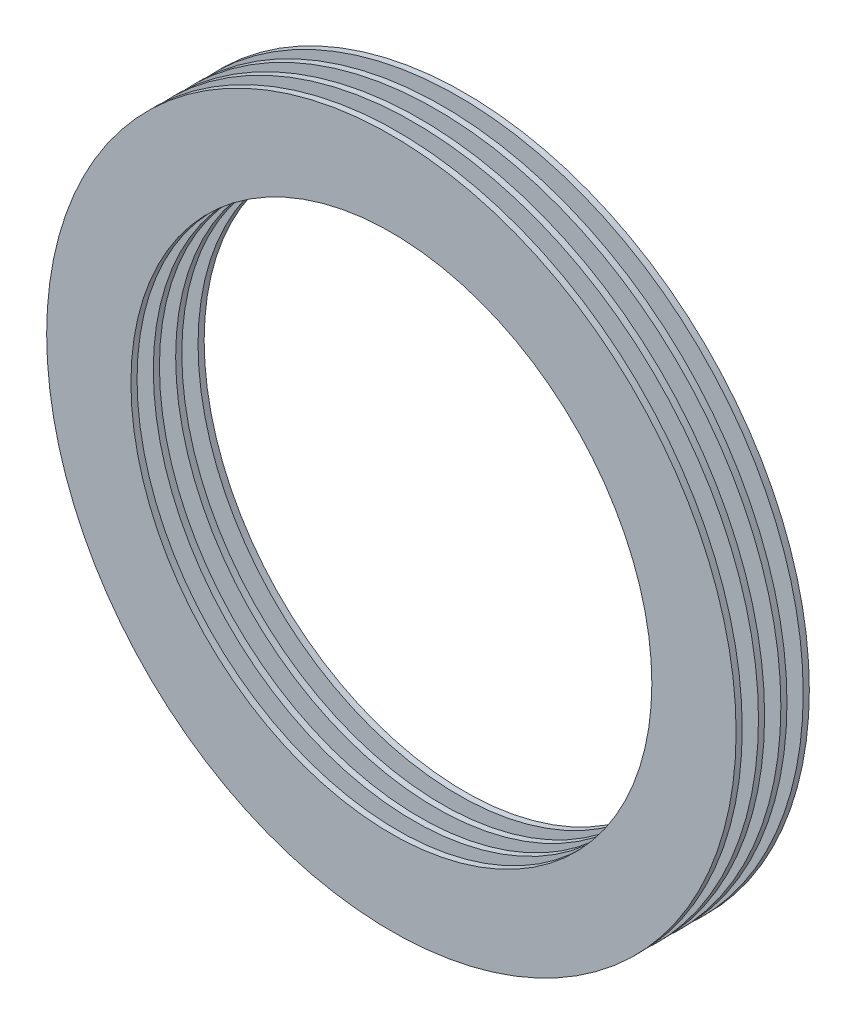
SolidWorks part; units mm, degrees
ref_plane "Front Plane" through (0, 0, 0) normal (0, 0, 1) x (1, 0, 0)
ref_plane "Top Plane" through (0, 0, 0) normal (0, 1, 0) x (1, 0, 0)
ref_plane "Right Plane" through (0, 0, 0) normal (1, 0, 0) x (0, 0, -1)
sketch "Sketch1" plane through (0, 0, 0) normal (0, 0, 1) x (1, 0, 0)
  circle A0 centre (0, 0) radius 14.2875
  circle A1 centre (0, 0) radius 10.795
  dimension "D1" = 28.575
  dimension "D2" = 21.59
extrude "Ring Extrude" add sketch "Sketch1" along normal blind 0.254 contours A0 A1
pattern_linear "LPattern1" count 4 spacing 0.9271 along (0, 0, 1) of bodies 101
equation "\"D3@LPattern1\"=0.146/4in"
